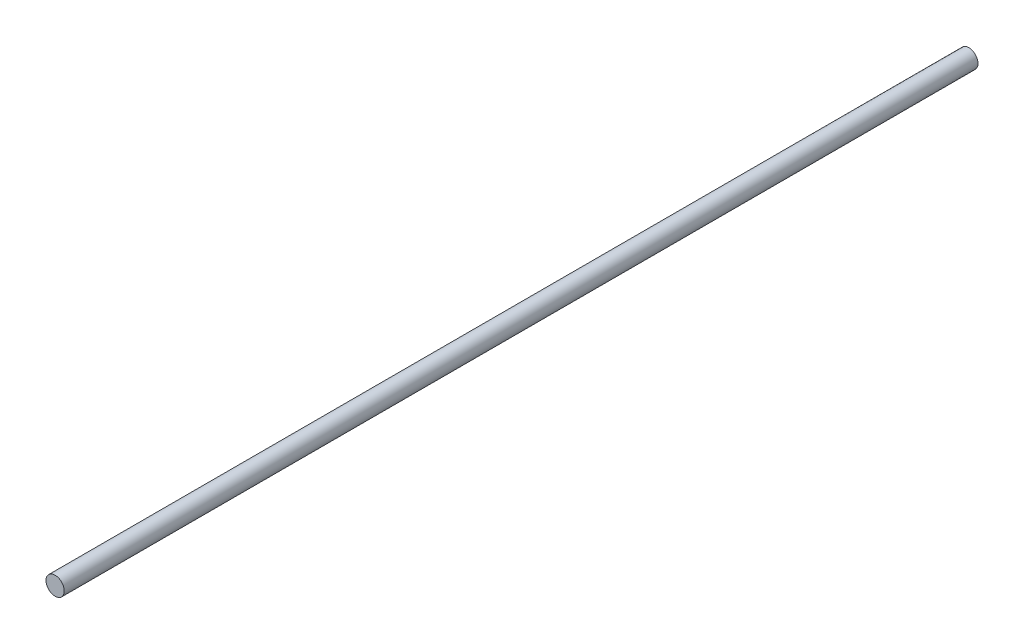
SolidWorks part; units mm, degrees
ref_plane "Front Plane" through (0, 0, 0) normal (0, 0, 1) x (1, 0, 0)
ref_plane "Top Plane" through (0, 0, 0) normal (0, 1, 0) x (1, 0, 0)
ref_plane "Right Plane" through (0, 0, 0) normal (1, 0, 0) x (0, 0, -1)
sketch "Sketch1" plane through (0, 0, 0) normal (0, 0, 1) x (1, 0, 0)
  circle A0 centre (0, 0) radius 1
  dimension "D1" = 2
extrude "Boss-Extrude1" add sketch "Sketch1" along normal mid plane 100
